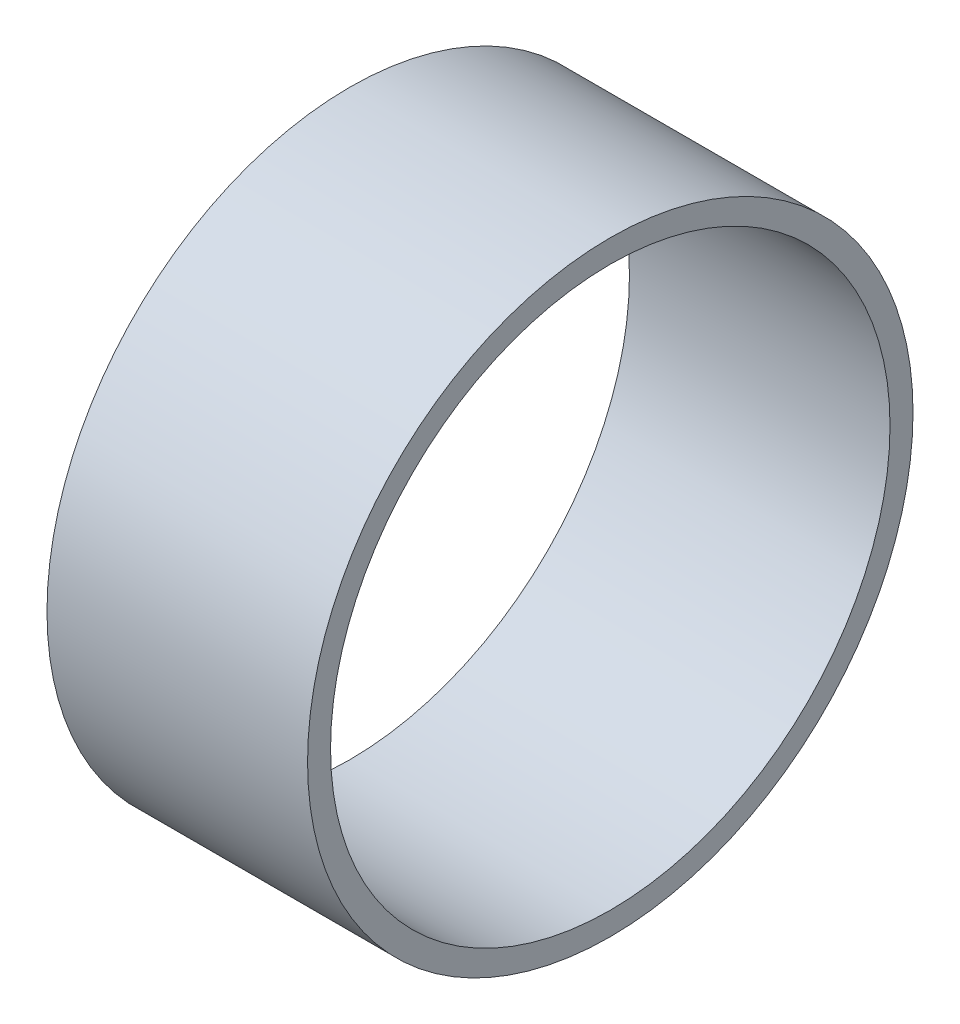
SolidWorks part; units mm, degrees
ref_plane "Front Plane" through (0, 0, 0) normal (0, 0, 1) x (1, 0, 0)
ref_plane "Top Plane" through (0, 0, 0) normal (0, 1, 0) x (1, 0, 0)
ref_plane "Right Plane" through (0, 0, 0) normal (1, 0, 0) x (0, 0, -1)
sketch "Sketch1" plane through (0, 0, 0) normal (1, 0, 0) x (0, 0, -1)
  circle A0 centre (0, 0) radius 18.25
  circle A2 centre (0, 0) radius 19.75
  dimension "D1" = 1.5
extrude "Boss-Extrude1" add sketch "Sketch1" along normal blind 17
